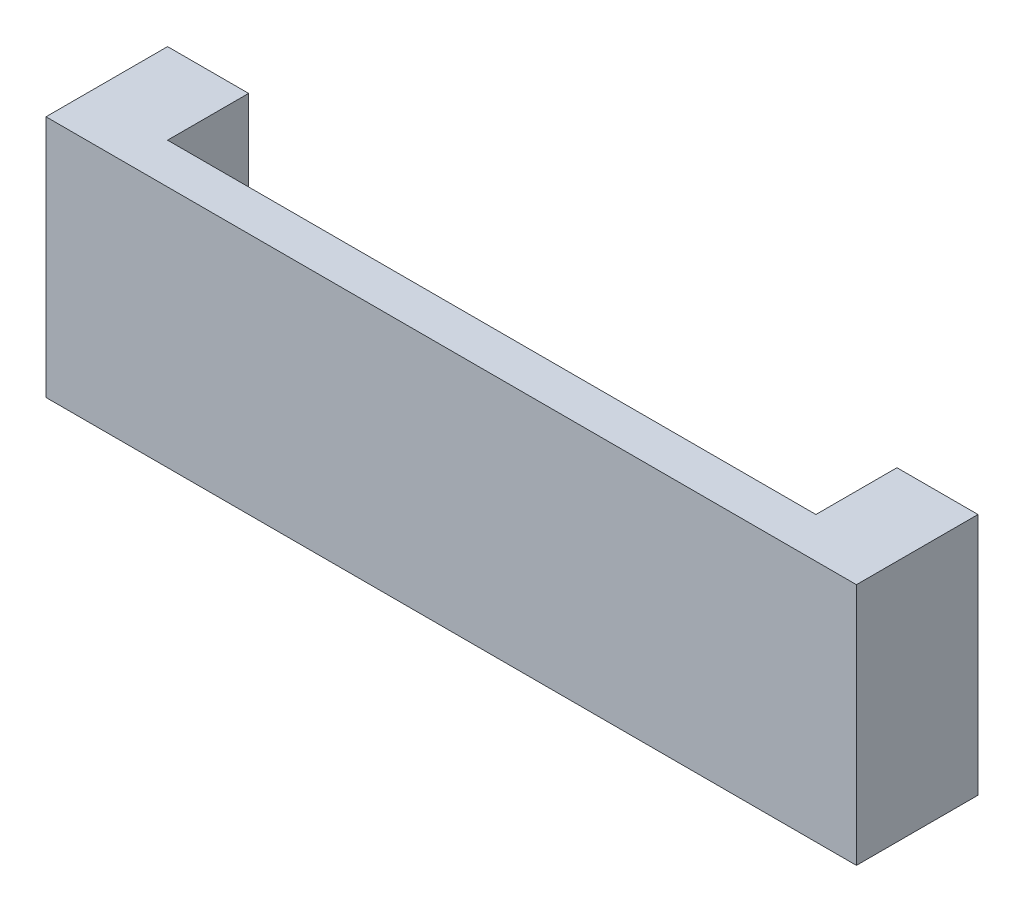
SolidWorks part; units mm, degrees
ref_plane "Přední rovina" through (0, 0, 0) normal (0, 0, 1) x (1, 0, 0)
ref_plane "Horní rovina" through (0, 0, 0) normal (0, 1, 0) x (1, 0, 0)
ref_plane "Pravá rovina" through (0, 0, 0) normal (1, 0, 0) x (0, 0, -1)
sketch "Sketch1" plane through (0, 0, 0) normal (0, 1, 0) x (1, 0, 0)
  line L1 (-50, 0) -> (-40, 0)
  line L2 (-50, 0) -> (-50, -15)
  line L3 (-50, -15) -> (50, -15)
  line L6 (-40, 0) -> (-40, -10)
  line L7 (-40, -10) -> (40, -10)
  line L9 (0, 0) -> (0, -15) construction
  line L10 (40, 0) -> (40, -10)
  line L11 (50, 0) -> (50, -15)
  line L12 (50, 0) -> (40, 0)
  point P3 (0, -10)
  dimension "D1" = 50
  dimension "D2" = 10
  dimension "D3" = 10
  dimension "D4" = 5
extrude "Boss-Extrude1" add sketch "Sketch1" along normal blind 30
